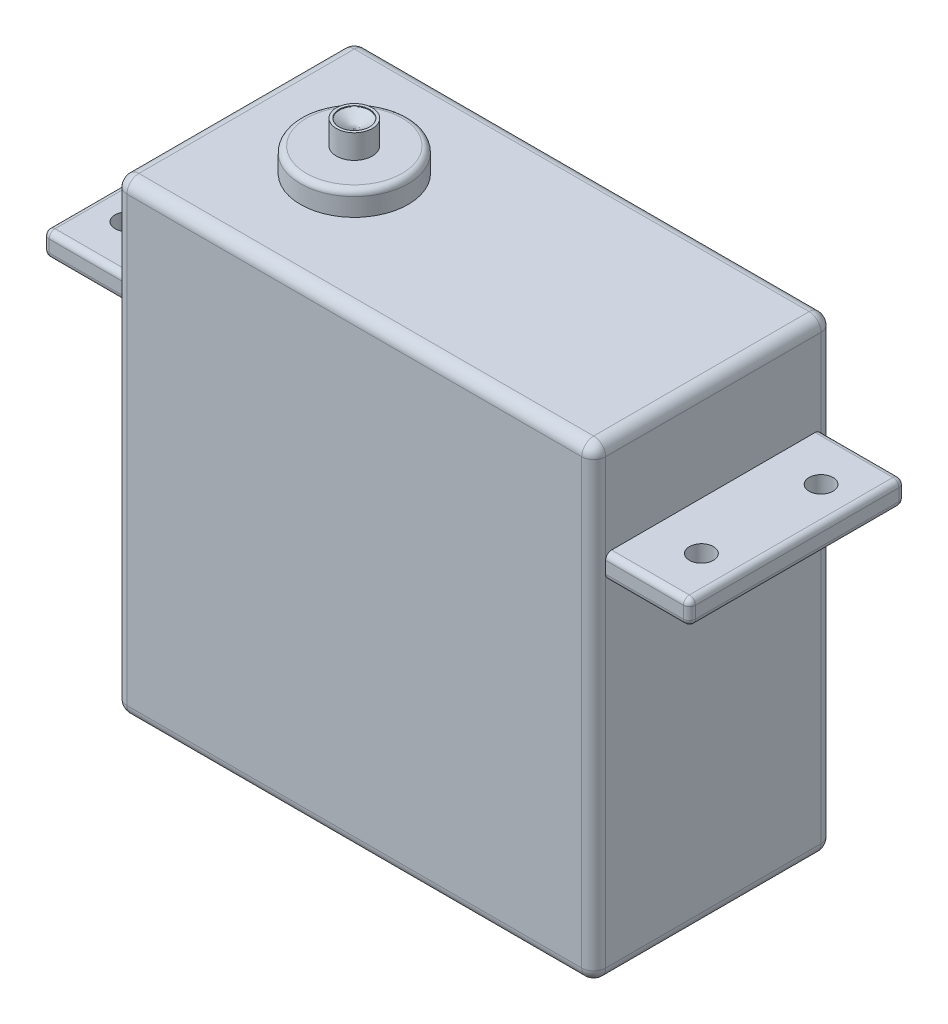
SolidWorks part; units mm, degrees
ref_plane "前视基准面" through (0, 0, 0) normal (0, 0, 1) x (1, 0, 0)
ref_plane "上视基准面" through (0, 0, 0) normal (0, 1, 0) x (1, 0, 0)
ref_plane "右视基准面" through (0, 0, 0) normal (1, 0, 0) x (0, 0, -1)
other "Configuration Table"
sketch "草图2" plane through (0, 0, 0) normal (0, 0, 1) x (1, 0, 0)
  line L1 (-41.6794, 29.0469) -> (-1.6794, 29.0469)
  line L2 (-41.6794, 29.0469) -> (-41.6794, -9.9531)
  line L3 (-41.6794, -9.9531) -> (-1.6794, -9.9531)
  line L4 (-1.6794, 29.0469) -> (-1.6794, -9.9531)
extrude "凸台-拉伸1" add sketch "草图2" along normal blind 20 contours L1 L4 L3 L2
fillet "圆角1" radius 1 12 edges at (-21.6794, -9.9531, 0) (-1.6794, 9.5469, 0) (-41.6794, 9.5469, 0) (-21.6794, 29.0469, 0) (-21.6794, -9.9531, 20) (-1.6794, 9.5469, 20) (-41.6794, 9.5469, 20) (-21.6794, 29.0469, 20) (-1.6794, 29.0469, 10) (-1.6794, -9.9531, 10) (-41.6794, -9.9531, 10) (-41.6794, 29.0469, 10)
sketch "草图7" plane through (-41.6794, 0, 0) normal (-1, 0, 0) x (0, 0, 1)
  line L1 (1, 28.0469) -> (1, -8.9531) construction
  line L2 (1, 21.0469) -> (19, 21.0469)
  line L3 (19, -8.9531) -> (19, 28.0469) construction
  line L4 (19, 21.0469) -> (19, 19.0469)
  line L5 (19, 19.0469) -> (1, 19.0469)
  line L6 (1, 19.0469) -> (1, 21.0469)
extrude "凸台-拉伸3" add sketch "草图7" along normal blind 7 contours L2 L4 L5 L6
sketch "草图8" plane through (-1.6794, 0, 0) normal (1, 0, 0) x (0, 0, -1)
  line L2 (-19, 28.0469) -> (-19, -8.9531) construction
  line L3 (-19, 21.0469) -> (-1, 21.0469)
  line L4 (-1, -8.9531) -> (-1, 28.0469) construction
  line L5 (-1, 21.0469) -> (-1, 19.0469)
  line L6 (-1, 19.0469) -> (-19, 19.0469)
  line L7 (-19, 19.0469) -> (-19, 21.0469)
extrude "凸台-拉伸4" add sketch "草图8" along normal blind 7
sketch "草图10" plane through (0, 21.0469, 0) normal (0, 1, 0) x (1, 0, 0)
  line L0 (-41.6794, -1) -> (-45.6794, -1)
  line L1 (-48.6794, -1) -> (-41.6794, -1) construction
  line L3 (-48.6794, -19) -> (-41.6794, -19) construction
  line L4 (-45.6794, -19) -> (-41.6794, -19)
  line L5 (-41.6794, -19) -> (-41.6794, -1)
  line L6 (-45.6794, -1) -> (-45.6794, -5)
  line L7 (-45.6794, -5) -> (-45.6794, -19)
  line L8 (-45.6794, -19) -> (-45.6794, -15)
  line L10 (-31.6794, -15) -> (-31.6794, -5)
  circle A0 centre (-45.6794, -5) radius 1
  circle A1 centre (-45.6794, -15) radius 1
sketch "草图11" plane through (0, 21.0469, 0) normal (0, 1, 0) x (1, 0, 0)
  line L0 (-1.6794, -1) -> (2.3206, -1)
  line L1 (5.3206, -1) -> (-1.6794, -1) construction
  line L2 (2.3206, -1) -> (2.3206, -19)
  line L3 (5.3206, -19) -> (-1.6794, -19) construction
  line L4 (2.3206, -19) -> (-1.6794, -19)
  line L5 (2.3206, -19) -> (2.3206, -15)
  line L6 (2.3206, -1) -> (2.3206, -5)
  circle A0 centre (2.3206, -5) radius 1
  circle A1 centre (2.3206, -15) radius 1
extrude "切除-拉伸2" cut sketch "草图11" against normal through all contours A1 | A0
sketch "草图12" plane through (0, 29.0469, 0) normal (0, 1, 0) x (1, 0, 0)
  line L0 (-31.6794, -15) -> (-31.6794, -5) construction
  circle A0 centre (-31.6794, -10) radius 4.5
extrude "凸台-拉伸5" add sketch "草图12" along normal blind 2 contours A0
sketch "草图13" plane through (0, 29.0469, 0) normal (0, 1, 0) x (1, 0, 0)
  line L0 (-31.6794, -15) -> (-31.6794, -5) construction
  circle A0 centre (-31.6794, -10) radius 1.5
extrude "凸台-拉伸6" add sketch "草图13" along normal blind 4
fillet "圆角2" radius 0.5 1 edges at (-31.6794, 31.0469, 14.5)
sketch "草图18" plane through (0, 33.0469, 0) normal (0, 1, 0) x (1, 0, 0)
  line L0 (-31.6794, -15) -> (-31.6794, -5) construction
  point P0 (-31.6794, -10)
hole_wizard "M3 螺纹孔的螺纹孔钻头1" positions "草图18" profile "草图17" hole size "M3" standard "ISO"
sketch "草图17" plane through (-31.6794, 33.0469, 10) normal (1, 0, 0) x (0, 0, 1)
  line L0 (0, 0) -> (0, 0.8011)
  line L1 (0, 0.8011) -> (1.25, 0.05)
  line L2 (1.25, 0.05) -> (1.25, 0.025)
  line L3 (1.25, 0.025) -> (1.275, 0)
  line L5 (1.275, 0) -> (0, 0)
  line L6 (-1.25, 0.025) -> (-1.275, 0) construction
  line L10 (0, 0.8011) -> (-1.25, 0.05) construction
  line L11 (0, -6.35) -> (0, 107.95) construction
  dimension "孔直径" = 2.5
  dimension "孔深度" = 0.05
  dimension "近端锥形沉头孔直径" = 2.55
  dimension "近端锥形沉头孔角度" = 90
  dimension "导头角度" = 118
fillet "圆角3" radius 0.5 8 edges at (-45.1794, 19.0469, 1) (-48.6794, 20.0469, 1) (-45.1794, 21.0469, 1) (-45.1794, 21.0469, 19) (-48.6794, 19.0469, 10) (-48.6794, 21.0469, 10) (-45.1794, 19.0469, 19) (-48.6794, 20.0469, 19)
fillet "圆角4" radius 0.5 8 edges at (5.3206, 20.0469, 1) (1.8206, 19.0469, 1) (1.8206, 21.0469, 1) (5.3206, 20.0469, 19) (5.3206, 19.0469, 10) (5.3206, 21.0469, 10) (1.8206, 19.0469, 19) (1.8206, 21.0469, 19)
extrude "切除-拉伸3" cut sketch "草图10" against normal through all contours A1 | A0
